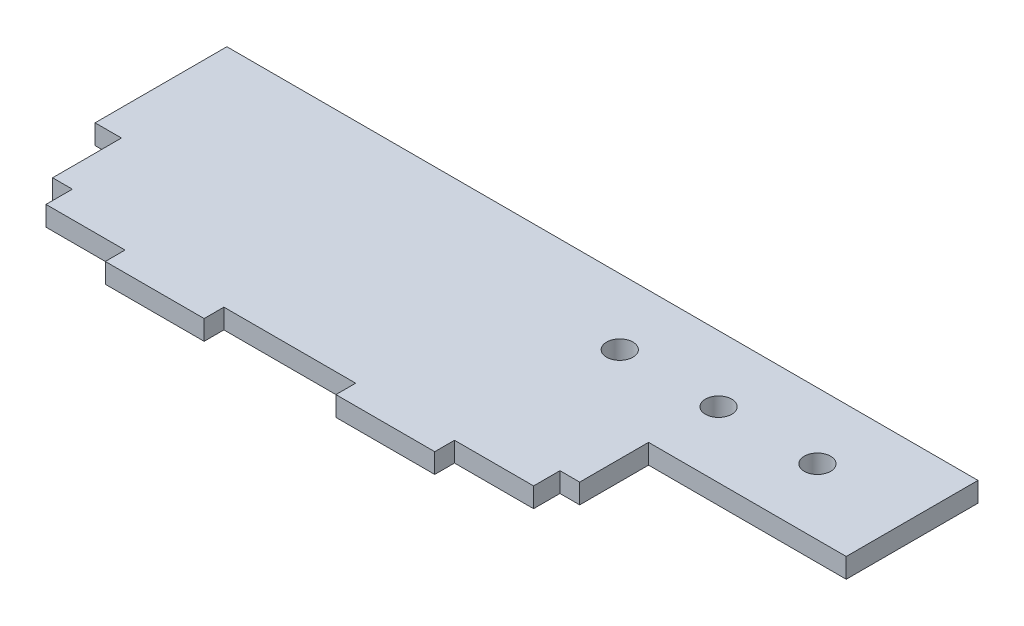
SolidWorks part; units mm, degrees
ref_plane "前视基准面" through (0, 0, 0) normal (0, 0, 1) x (1, 0, 0)
ref_plane "上视基准面" through (0, 0, 0) normal (0, 1, 0) x (1, 0, 0)
ref_plane "右视基准面" through (0, 0, 0) normal (1, 0, 0) x (0, 0, -1)
other "Configuration Table"
sketch "草图1" plane through (0, 0, 0) normal (0, 1, 0) x (1, 0, 0)
  line L0 (0, 7.177) -> (0, -18.2347) construction
  line L1 (-40, 17.225) -> (40, 17.225)
  line L2 (-40, 17.225) -> (-40, -17.225)
  line L3 (-40, -17.225) -> (40, -17.225)
  line L4 (40, 17.225) -> (40, -17.225)
  line L5 (-40, 17.225) -> (40, -17.225) construction
  line L6 (-40, -17.225) -> (40, 17.225) construction
  line L7 (-25, -17.225) -> (-10, -17.225)
  line L8 (-25, -17.225) -> (-25, -20.225)
  line L9 (-25, -20.225) -> (-10, -20.225)
  line L10 (-10, -17.225) -> (-10, -20.225)
  line L11 (25, -20.225) -> (10, -20.225)
  line L12 (10, -17.225) -> (10, -20.225)
  line L13 (25, -17.225) -> (10, -17.225)
  line L14 (25, -17.225) -> (25, -20.225)
  line L20 (-40, 17.225) -> (-44, 17.225)
  line L21 (-40, 17.225) -> (-40, -2.775)
  line L22 (-40, -2.775) -> (-44, -2.775)
  line L23 (-44, 17.225) -> (-44, -2.775)
  line L24 (40, 17.225) -> (70, 17.225)
  line L25 (40, 17.225) -> (40, -2.775)
  line L26 (40, -2.775) -> (70, -2.775)
  line L27 (70, 17.225) -> (70, -2.775)
  point P0 (0, 0)
  dimension "D1" = 34.45
  dimension "D2" = 80
  dimension "D3" = 3
  dimension "D4" = 15
  dimension "D5" = 10
  dimension "D6" = 20
  dimension "D7" = 30
  dimension "D8" = 4
extrude "凸台-拉伸1" add sketch "草图1" along normal blind 3
sketch "草图2" plane through (0, 3, 0) normal (0, 1, 0) x (1, 0, 0)
  line L0 (70, 17.225) -> (70, -2.775) construction
  line L1 (40, -2.775) -> (70, -2.775) construction
  circle A0 centre (55.63, 7.225) radius 2
  circle A1 centre (40.63, 7.225) radius 2
  circle A2 centre (25.63, 7.225) radius 2
  dimension "D2" = 4
  dimension "D4" = 15
  dimension "D1" = 10
  dimension "D5" = 14.37
  dimension "D3" = 3
extrude "切除-拉伸1" cut sketch "草图2" against normal blind 10
sketch "草图3" plane through (0, 3, 0) normal (0, 1, 0) x (1, 0, 0)
  line L1 (-40, -17.225) -> (-37, -17.225)
  line L2 (-40, -17.225) -> (-40, -13.225)
  line L3 (-40, -13.225) -> (-37, -13.225)
  line L4 (-37, -17.225) -> (-37, -13.225)
  line L5 (40, -17.225) -> (37, -17.225)
  line L6 (40, -17.225) -> (40, -13.225)
  line L7 (40, -13.225) -> (37, -13.225)
  line L8 (37, -17.225) -> (37, -13.225)
  dimension "D1" = 3
  dimension "D2" = 4
extrude "切除-拉伸2" cut sketch "草图3" against normal blind 3
